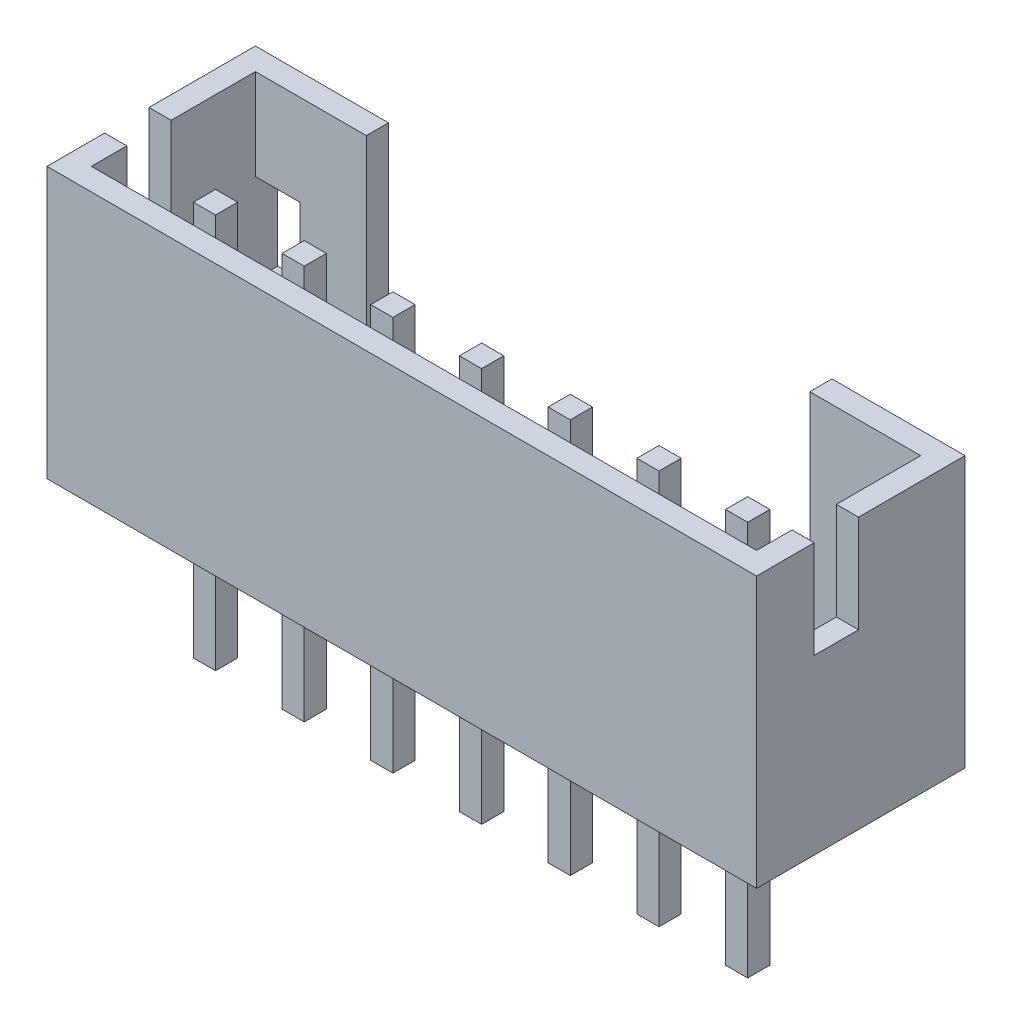
SolidWorks part; units mm, degrees
ref_plane "Front Plane" through (0, 0, 0) normal (0, 0, 1) x (1, 0, 0)
ref_plane "Top Plane" through (0, 0, 0) normal (0, 1, 0) x (1, 0, 0)
ref_plane "Right Plane" through (0, 0, 0) normal (1, 0, 0) x (0, 0, -1)
sketch "Sketch1" plane through (0, 0, 0) normal (0, 1, 0) x (1, 0, 0)
  line L1 (-8, -2.35) -> (8, -2.35)
  line L2 (-8, -2.35) -> (-8, 2.35)
  line L3 (-8, 2.35) -> (8, 2.35)
  line L4 (8, -2.35) -> (8, 2.35)
  line L5 (-8, -2.35) -> (8, 2.35) construction
  line L6 (-8, 2.35) -> (8, -2.35) construction
  point P0 (0, 0)
  dimension "D1" = 4.7
  dimension "D2" = 16
extrude "casing" add sketch "Sketch1" along normal blind 6.1
shell "casing_shell" thickness 0.5
sketch "Sketch2" plane through (0, 0.5, 0) normal (0, 1, 0) x (1, 0, 0)
  line L0 (-7.5, -0.55) -> (7.5, -0.55) construction
  line L1 (-7.5, 1.85) -> (-7.5, -1.85) construction
  line L2 (7.5, -1.85) -> (7.5, 1.85) construction
  line L3 (-8, -2.35) -> (8, -2.35) construction
  line L5 (-6.25, -0.3) -> (-5.75, -0.3)
  line L6 (-6.25, -0.3) -> (-6.25, -0.8)
  line L7 (-6.25, -0.8) -> (-5.75, -0.8)
  line L8 (-5.75, -0.3) -> (-5.75, -0.8)
  line L9 (-6.25, -0.3) -> (-5.75, -0.8) construction
  line L10 (-6.25, -0.8) -> (-5.75, -0.3) construction
  line L11 (-4.25, -0.3) -> (-4.25, -0.8)
  line L12 (-4.25, -0.3) -> (-3.75, -0.3)
  line L13 (-3.75, -0.3) -> (-3.75, -0.8)
  line L14 (-4.25, -0.8) -> (-3.75, -0.8)
  line L15 (-2.25, -0.3) -> (-2.25, -0.8)
  line L16 (-2.25, -0.3) -> (-1.75, -0.3)
  line L17 (-1.75, -0.3) -> (-1.75, -0.8)
  line L18 (-2.25, -0.8) -> (-1.75, -0.8)
  line L19 (-0.25, -0.3) -> (-0.25, -0.8)
  line L20 (-0.25, -0.3) -> (0.25, -0.3)
  line L21 (0.25, -0.3) -> (0.25, -0.8)
  line L22 (-0.25, -0.8) -> (0.25, -0.8)
  line L23 (1.75, -0.3) -> (1.75, -0.8)
  line L24 (1.75, -0.3) -> (2.25, -0.3)
  line L25 (2.25, -0.3) -> (2.25, -0.8)
  line L26 (1.75, -0.8) -> (2.25, -0.8)
  line L27 (3.75, -0.3) -> (3.75, -0.8)
  line L28 (3.75, -0.3) -> (4.25, -0.3)
  line L29 (4.25, -0.3) -> (4.25, -0.8)
  line L30 (3.75, -0.8) -> (4.25, -0.8)
  line L31 (5.75, -0.3) -> (5.75, -0.8)
  line L32 (5.75, -0.3) -> (6.25, -0.3)
  line L33 (6.25, -0.3) -> (6.25, -0.8)
  line L34 (5.75, -0.8) -> (6.25, -0.8)
  line L35 (-6.25, -0.3) -> (-4.25, -0.3) construction
  point P8 (-6, -0.55)
  point P13 (0, -0.3)
  dimension "D1" = 1.8
  dimension "D2" = 0.5
  dimension "D5" = 2
  dimension "D4" = 7
extrude "pins" add sketch "Sketch2" along normal blind 5 and the other way blind 3.9 separate body
sketch "Sketch3" plane through (0, 0, -2.35) normal (0, 0, -1) x (-1, 0, 0)
  line L0 (-8, 6.1) -> (8, 6.1) construction
  line L1 (-5, 6.1) -> (5, 6.1)
  line L2 (-5, 6.1) -> (-5, 1.5)
  line L3 (-5, 1.5) -> (5, 1.5)
  line L4 (5, 6.1) -> (5, 1.5)
  line L5 (-5.75, -3.4) -> (-5.75, 5.5) construction
  line L7 (-8, 0) -> (8, 0) construction
  line L8 (-8, 6.1) -> (-8, 0) construction
  line L9 (-6.5, 2.05) -> (-7.5, 2.05)
  line L10 (-6.5, 2.05) -> (-6.5, 4.05)
  line L11 (-6.5, 4.05) -> (-7.5, 4.05)
  line L12 (-7.5, 2.05) -> (-7.5, 4.05)
  line L13 (-6.5, 2.05) -> (-7.5, 4.05) construction
  line L14 (-6.5, 4.05) -> (-7.5, 2.05) construction
  line L15 (0, 2.585) -> (0, -2.585) construction
  line L16 (6.5, 4.05) -> (7.5, 4.05)
  line L17 (7.5, 2.05) -> (7.5, 4.05)
  line L18 (6.5, 2.05) -> (7.5, 2.05)
  line L19 (6.5, 2.05) -> (6.5, 4.05)
  point P10 (-7, 3.05)
  point P18 (-8, 3.05)
  dimension "D1" = 0.75
  dimension "D2" = 10
  dimension "D3" = 1.5
  dimension "D4" = 1
  dimension "D5" = 2
  dimension "D6" = 0.5
extrude "shape_cut1" cut sketch "Sketch3" against normal up to surface (0.5 mm away) up to face at (0, 3.3, -1.85)
sketch "Sketch4" plane through (-8, 0, 0) normal (-1, 0, 0) x (0, 0, 1)
  line L0 (-2.35, 6.1) -> (2.35, 6.1) construction
  line L1 (1.05, 3.9) -> (0.05, 3.9)
  line L2 (1.05, 3.9) -> (1.05, 6.1)
  line L3 (1.05, 6.1) -> (0.05, 6.1)
  line L4 (0.05, 3.9) -> (0.05, 6.1)
  line L5 (1.05, 3.9) -> (0.05, 6.1) construction
  line L6 (1.05, 6.1) -> (0.05, 3.9) construction
  line L7 (-2.35, 0) -> (2.35, 0) construction
  line L8 (-2.35, 6.1) -> (-2.35, 0) construction
  point P0 (0.55, 5)
  dimension "D1" = 5
  dimension "D2" = 1
  dimension "D3" = 2.4
extrude "shape_cut2" cut sketch "Sketch4" against normal up to surface (15.5 mm away)
mirror "shape_cut2m" about plane through (0, 0, 0) normal (1, 0, 0) of "shape_cut2"
